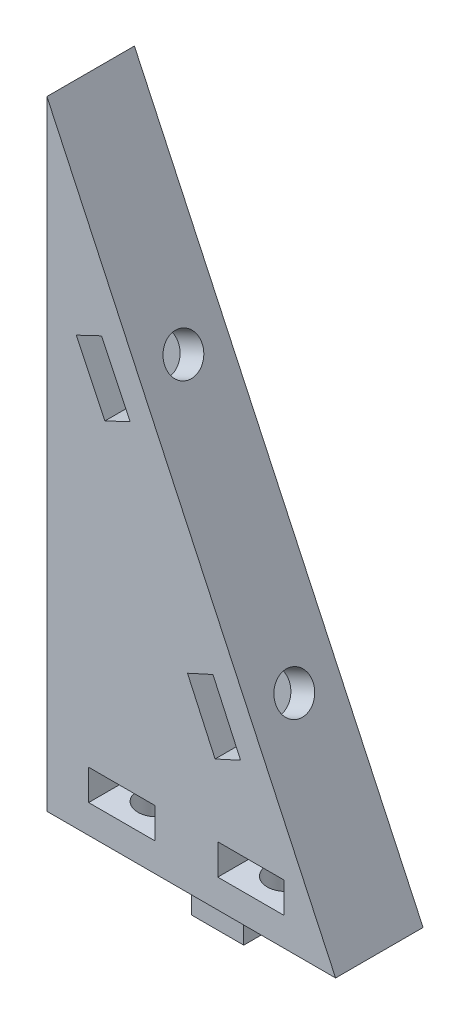
SolidWorks part; units mm, degrees
ref_plane "Front" through (0, 0, 0) normal (0, 0, 1) x (1, 0, 0)
ref_plane "Top" through (0, 0, 0) normal (0, 1, 0) x (1, 0, 0)
ref_plane "Right" through (0, 0, 0) normal (1, 0, 0) x (0, 0, -1)
sketch "Sketch1" plane through (0, 0, 0) normal (0, 0, 1) x (1, 0, 0)
  line L0 (0, 70.7687) -> (0, 0)
  line L1 (0, 0) -> (33, 0)
  line L2 (33, 0) -> (0, 70.7687)
  dimension "D1" = 33
  dimension "D2" = 65
extrude "Boss-Extrude1" add sketch "Sketch1" along normal blind 10
sketch "Sketch2" plane through (0, 0, 0) normal (0, -1, 0) x (-1, 0, 0)
  line L0 (-16.5, -10) -> (-16.5, 0) construction
  line L1 (-13.5, -7) -> (-19.5, -7)
  line L2 (-13.5, -7) -> (-13.5, -3)
  line L3 (-13.5, -3) -> (-19.5, -3)
  line L4 (-19.5, -7) -> (-19.5, -3)
  line L5 (-13.5, -7) -> (-19.5, -3) construction
  line L6 (-13.5, -3) -> (-19.5, -7) construction
  line L7 (0, -10) -> (-33, -10) construction
  line L8 (0, 0) -> (-33, 0) construction
  line L9 (0, -5) -> (-33, -5) construction
  line L10 (0, -10) -> (0, 0) construction
  line L11 (-33, -10) -> (-33, 0) construction
  point P0 (-16.5, -5)
  point P18 (-16.5, -5)
  dimension "D1" = 6
  dimension "D2" = 4
extrude "Boss-Extrude2" add sketch "Sketch2" along normal blind 5
sketch "Sketch3" plane through (0, 0, 0) normal (0, -1, 0) x (-1, 0, 0)
  line L3 (0, -10) -> (-33, -10) construction
  line L4 (-33, -10) -> (-33, 0) construction
  circle A2 centre (-23.33, -6) radius 2.15
  circle A3 centre (-8.55, -6) radius 2.15
  dimension "D1" = 4.3
  dimension "D2" = 4
  dimension "D3" = 9.67
  dimension "D4" = 14.78
  dimension "D5" = 4
extrude "Cut-Extrude1" cut sketch "Sketch3" against normal blind 12
sketch "Sketch4" plane through (0, 0, 0) normal (0, 0, -1) x (-1, 0, 0)
  line L0 (-27.13, 3.2517) -> (-27.13, 5) construction
  line L1 (-25.4815, -1.25) -> (-21.1815, -1.25) construction
  line L2 (-19.53, 3.2517) -> (-19.53, 5) construction
  line L3 (-25.48, 0) -> (-21.18, 0)
  line L4 (-21.18, 0) -> (-10.7, 0) construction
  line L5 (-15.94, 0) -> (-15.94, 7.9966) construction
  line L7 (-12.35, 3.2517) -> (-12.35, 5) construction
  line L8 (-25.4815, 0) -> (-25.4815, -2.5) construction
  line L13 (-23.33, 5) -> (-23.33, -5) construction
  line L14 (-35.3315, -5) -> (66.6685, -5) construction
  line L15 (-21.1815, -2.5) -> (-21.1815, 0) construction
  line L20 (-27.13, 3.2517) -> (-19.53, 3.2517)
  line L21 (-19.53, 3.2517) -> (-19.53, 6.7517)
  line L22 (-19.53, 6.7517) -> (-27.13, 6.7517)
  line L23 (-27.13, 6.7517) -> (-27.13, 3.2517)
  line L24 (-27.13, 5) -> (-19.53, 5) construction
  line L25 (-4.75, 3.2517) -> (-4.75, 5) construction
  line L26 (-4.75, 6.7517) -> (-4.75, 3.2517)
  line L27 (-12.35, 6.7517) -> (-4.75, 6.7517)
  line L28 (-12.35, 3.2517) -> (-12.35, 6.7517)
  line L29 (-4.75, 3.2517) -> (-12.35, 3.2517)
  point P5 (-23.33, 0)
  dimension "D1" = 7.6
  dimension "D2" = 3.8
  dimension "D3" = 3.5
sketch "Sketch6" plane through (27.106, 12.6397, 0) normal (0.9063, 0.4226, 0) x (0, 0, -1)
  line L0 (0, -13.9464) -> (0, 64.1382) construction
  line L1 (-10, -13.9464) -> (0, -13.9464) construction
  circle A0 centre (-5, 9.0536) radius 2.15
  circle A1 centre (-5, 39.0536) radius 2.15
  dimension "D3" = 4.3
  dimension "D4" = 23
  dimension "D1" = 5
  dimension "D2" = 5
  dimension "D5" = 53
extrude "Cut-Extrude4" cut sketch "Sketch6" against normal blind 7.3
extrude "Cut-Extrude5" cut sketch "Sketch4" along normal blind 6.5 from surface at -10 contours L23 L20 L21 L22 starting at face at (11, 23.5896, 10)
sketch "Sketch7" plane through (0, 0, 10) normal (0, 0, 1) x (1, 0, 0)
  line L0 (19.53, 6.7517) -> (19.53, 3.2517)
  line L1 (19.53, 3.2517) -> (27.13, 3.2517)
  line L2 (27.13, 3.2517) -> (27.13, 6.7517)
  line L3 (27.13, 6.7517) -> (19.53, 6.7517)
  line L4 (23.33, 3.2517) -> (23.33, 0)
  line L5 (0, 0) -> (33, 0) construction
  line L6 (23.33, 0) -> (15.949, 0)
  line L8 (15.949, 0) -> (15.949, 7.1074) construction
  line L9 (4.7679, 6.7517) -> (12.3679, 6.7517)
  line L10 (4.7679, 3.2517) -> (4.7679, 6.7517)
  line L11 (12.3679, 3.2517) -> (4.7679, 3.2517)
  line L12 (12.3679, 6.7517) -> (12.3679, 3.2517)
extrude "Cut-Extrude6" cut sketch "Sketch7" against normal blind 6.5 contours L12 L9 L10 L11
sketch "Sketch9" plane through (0, 0, 10) normal (0, 0, 1) x (1, 0, 0)
  line L0 (10.4481, 50.7255) -> (9.5418, 50.3029) construction
  line L1 (-0.0009, 70.7673) -> (35.33, -5) construction
  line L2 (10.4481, 50.7255) -> (9.5418, 50.3029) construction
  line L3 (9.5418, 50.3029) -> (11.6562, 45.772) construction
  line L4 (33, 0) -> (0, 70.7687) construction
  line L5 (11.6562, 45.772) -> (12.5612, 46.194) construction
  line L6 (12.5612, 46.194) -> (10.4481, 50.7255) construction
  line L7 (10.599, 48.0374) -> (1.7486, 43.9074) construction
  line L8 (7.8804, 46.7688) -> (6.246, 50.1994)
  line L9 (6.246, 50.1994) -> (3.3571, 48.823)
  line L10 (3.3571, 48.823) -> (6.626, 41.9619)
  line L11 (6.626, 41.9619) -> (9.5149, 43.3383)
  line L12 (9.5149, 43.3383) -> (7.8804, 46.7688)
  line L13 (11.6562, 45.772) -> (22.2216, 23.1143) construction
  line L14 (23.1267, 23.5363) -> (22.2204, 23.1137) construction
  line L15 (22.2216, 23.1143) -> (23.1267, 23.5363) construction
  line L16 (16.9389, 34.4431) -> (7.737, 30.1522) construction
  line L17 (18.9809, 23.0383) -> (20.5583, 19.5811)
  line L18 (16.0696, 21.7099) -> (18.9809, 23.0383)
  line L19 (19.2244, 14.7956) -> (16.0696, 21.7099)
  line L20 (22.1356, 16.1239) -> (19.2244, 14.7956)
  line L21 (20.5583, 19.5811) -> (22.1356, 16.1239)
  dimension "D1" = 5
  dimension "D2" = 90
  dimension "D3" = 3.2
  dimension "D4" = 3.8
  dimension "D5" = 3.8
  dimension "D6" = 3
  dimension "D7" = 90
extrude "Cut-Extrude7" cut sketch "Sketch9" against normal blind 7.5
